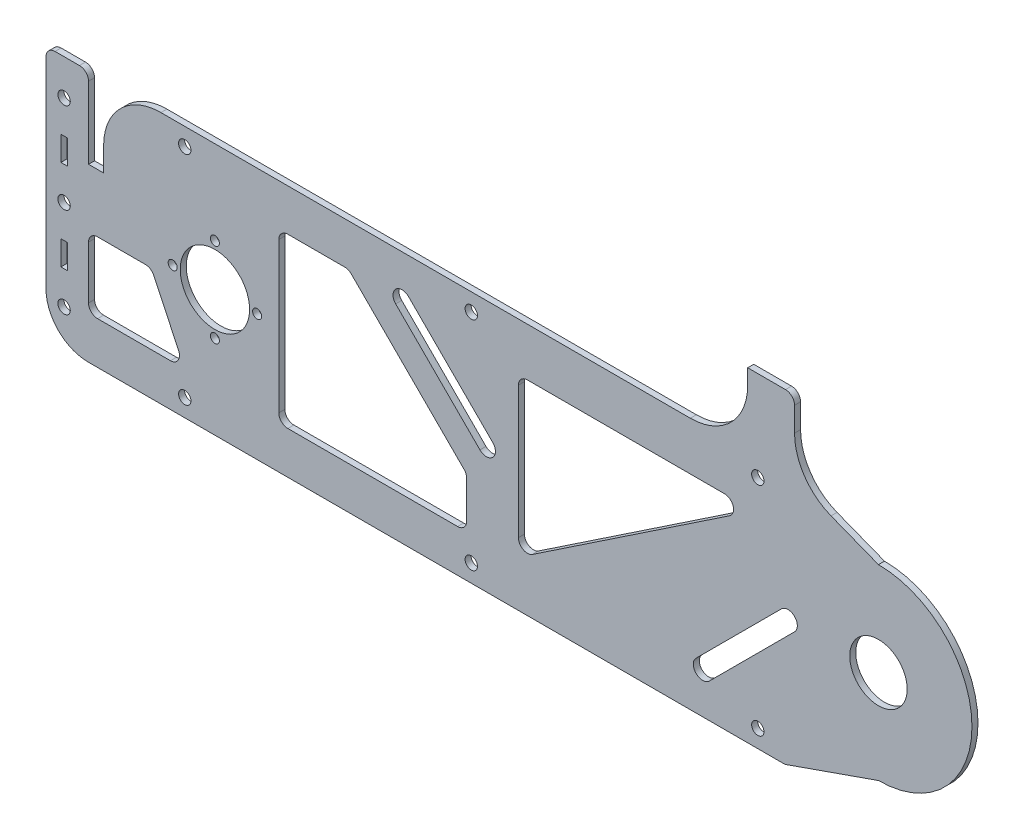
SolidWorks part; units mm, degrees
ref_plane "前视基准面" through (0, 0, 0) normal (0, 0, 1) x (1, 0, 0)
ref_plane "上视基准面" through (0, 0, 0) normal (0, 1, 0) x (1, 0, 0)
ref_plane "右视基准面" through (0, 0, 0) normal (1, 0, 0) x (0, 0, -1)
sketch "草图1" plane through (0, 0, 0) normal (0, 0, 1) x (1, 0, 0)
  line L0 (1.6429, 32.0043) -> (1.6429, 27.9043) construction
  line L1 (1.6429, 18.9543) -> (1.6429, 10.9543) construction
  line L2 (0.5929, 10.9043) -> (2.6929, 10.9043)
  line L3 (0.5929, 10.9043) -> (0.5929, 19.0043)
  line L4 (0.5929, 19.0043) -> (2.6929, 19.0043)
  line L5 (2.6929, 10.9043) -> (2.6929, 19.0043)
  line L6 (0.5929, 10.9043) -> (2.6929, 19.0043) construction
  line L7 (0.5929, 19.0043) -> (2.6929, 10.9043) construction
  line L12 (1.6429, -0.0457) -> (-4.3571, -0.0457) construction
  line L13 (-4.3571, -0.0457) -> (-4.3571, 41.8043)
  line L14 (-4.3571, 41.8043) -> (302.6429, 41.8043) construction
  line L15 (302.6429, 41.8043) -> (302.6429, -38.1957) construction
  line L18 (51.6429, -0.0457) -> (97.8433, -0.0457) construction
  line L19 (51.6429, -0.0457) -> (271.6429, -0.0457) construction
  line L29 (1.6429, -0.0457) -> (37.6429, -0.0457) construction
  line L48 (0.5929, -19.0957) -> (2.6929, -10.9957) construction
  line L49 (0.5929, -10.9957) -> (2.6929, -19.0957) construction
  line L50 (1.6429, -19.0457) -> (1.6429, -11.0457) construction
  line L51 (2.6929, -10.9957) -> (2.6929, -19.0957)
  line L52 (0.5929, -19.0957) -> (2.6929, -19.0957)
  line L53 (0.5929, -10.9957) -> (0.5929, -19.0957)
  line L54 (0.5929, -10.9957) -> (2.6929, -10.9957)
  line L59 (-4.3571, -0.0457) -> (-4.3571, -41.8957)
  line L60 (-4.3571, -41.8957) -> (240.6429, -41.8957)
  line L61 (240.6429, -41.8957) -> (271.6429, -31.0457)
  line L63 (141.6429, -0.0457) -> (92.8665, 48.7307) construction
  line L64 (141.6429, -0.0457) -> (113.6929, 27.9043) construction
  line L67 (241.6429, -0.0457) -> (213.3586, -28.33)
  line L70 (139.5215, -2.167) -> (111.5715, 25.783)
  line L71 (143.7642, 2.0756) -> (115.8142, 30.0256)
  line L72 (-4.3571, 41.8043) -> (9.7429, 41.8043)
  line L73 (9.7429, 41.8043) -> (9.7429, 14.9543)
  line L74 (9.7429, 14.9543) -> (14.7429, 14.9543)
  line L75 (14.7429, 14.9543) -> (14.7429, 41.8043)
  line L82 (95.9658, 27.9043) -> (135.1225, -11.2524)
  line L83 (135.1225, -11.2524) -> (135.1225, -27.8677)
  line L84 (135.1225, -27.8677) -> (72.8282, -27.8677)
  line L85 (72.8282, -27.8677) -> (72.8282, 27.9043)
  line L86 (72.8282, 27.9043) -> (95.9658, 27.9043)
  line L87 (9.7429, -4.3892) -> (30.5295, -4.3892)
  line L88 (30.5295, -4.3892) -> (41.6429, -27.8677)
  line L89 (41.6429, -27.8677) -> (9.7429, -27.8677)
  line L90 (9.7429, -27.8677) -> (9.7429, -4.3892)
  line L95 (228.286, 41.8043) -> (14.7429, 41.8043)
  line L98 (228.286, 65.8043) -> (228.286, 41.8043)
  line L100 (243.8213, 41.8043) -> (243.8213, 65.8043)
  line L101 (228.286, 65.8043) -> (243.8213, 65.8043)
  line L102 (243.8213, 41.8043) -> (271.6429, 30.9543)
  line L103 (152.2591, -26.6039) -> (230.4644, 25.783)
  line L104 (230.4644, 25.783) -> (152.2591, 25.783)
  line L105 (152.2591, 25.783) -> (152.2591, -26.6039)
  line L106 (241.6429, -0.0457) -> (213.3586, -28.33) construction
  line L107 (243.8339, -2.2367) -> (215.5496, -30.521)
  line L108 (239.4519, 2.1453) -> (211.1676, -26.139)
  circle A0 centre (1.6429, 29.9543) radius 2.05
  circle A1 centre (1.6429, -0.0457) radius 2.05
  circle A2 centre (1.6429, -30.0457) radius 2.05
  circle A3 centre (51.6429, -0.0457) radius 11.5
  circle A4 centre (51.6429, -0.0457) radius 14 construction
  circle A5 centre (51.6429, -14.0457) radius 1.5
  circle A12 centre (37.6429, -0.0457) radius 1.5
  circle A13 centre (51.6429, 13.9543) radius 1.5
  circle A14 centre (65.6429, -0.0457) radius 1.5
  circle A15 centre (271.6429, -0.0457) radius 9.525
  circle A16 centre (271.6429, -0.0457) radius 31 construction
  arc A17 (271.6429, 30.9543) -> (271.6429, -31.0457) centre (271.6429, -0.0457) cw
  circle A18 centre (41.6429, 35.9543) radius 2.05
  circle A19 centre (136.6429, 35.9543) radius 2.05
  circle A20 centre (231.6429, 35.9543) radius 2.05
  circle A21 centre (136.6429, -36.0457) radius 2.05
  circle A22 centre (231.6429, -36.0457) radius 2.05
  circle A23 centre (41.6429, -36.0457) radius 2.05
  circle A24 centre (241.6429, -0.0457) radius 3.1 construction
  arc A31 (139.5215, -2.167) -> (143.7642, 2.0756) centre (141.6429, -0.0457) ccw
  arc A32 (115.8142, 30.0256) -> (111.5715, 25.783) centre (113.6929, 27.9043) ccw
  arc A33 (243.8339, -2.2367) -> (239.4519, 2.1453) centre (241.6429, -0.0457) ccw
  arc A34 (211.1676, -26.139) -> (215.5496, -30.521) centre (213.3586, -28.33) ccw
  point P6 (1.6429, 14.9543)
  point P49 (227.5007, -14.1878)
  point P56 (1.6429, -15.0457)
  point P68 (127.6679, 13.9293)
  dimension "D3" = 23
  dimension "D4" = 4
  dimension "D10" = 6
  dimension "D13" = 19.05
  dimension "D16" = 2
  dimension "D6" = 40
  dimension "D17" = 45
  dimension "D19" = 8.1
  dimension "D1" = 8.1
  dimension "D2" = 2.1
  dimension "D5" = 50
  dimension "D7" = 15
  dimension "D8" = 60
  dimension "D9" = 30
  dimension "D11" = 41.85
  dimension "D12" = 31
  dimension "D14" = 220
  dimension "D15" = 3
  dimension "D18" = 45
  dimension "D20" = 5
extrude "凸台-拉伸1" add sketch "草图1" along normal blind 2
fillet "圆角2" radius 3 13 edges at (152.2591, 25.783, 1) (95.9658, 27.9043, 1) (135.1225, -11.2524, 1) (135.1225, -27.8677, 1) (72.8282, -27.8677, 1) (72.8282, 27.9043, 1) (41.6429, -27.8677, 1) (30.5295, -4.3892, 1) (9.7429, -27.8677, 1) (9.7429, -4.3892, 1) (243.8213, 65.8043, 1) (230.4644, 25.783, 1) (152.2591, -26.6039, 1)
fillet "圆角3" radius 19 3 edges at (228.286, 41.8043, 1) (14.7429, 41.8043, 1) (243.8213, 41.8043, 1)
fillet "圆角4" radius 14 1 edges at (-4.3571, -41.8957, 1)
fillet "圆角5" radius 3 2 edges at (9.7429, 41.8043, 1) (-4.3571, 41.8043, 1)
